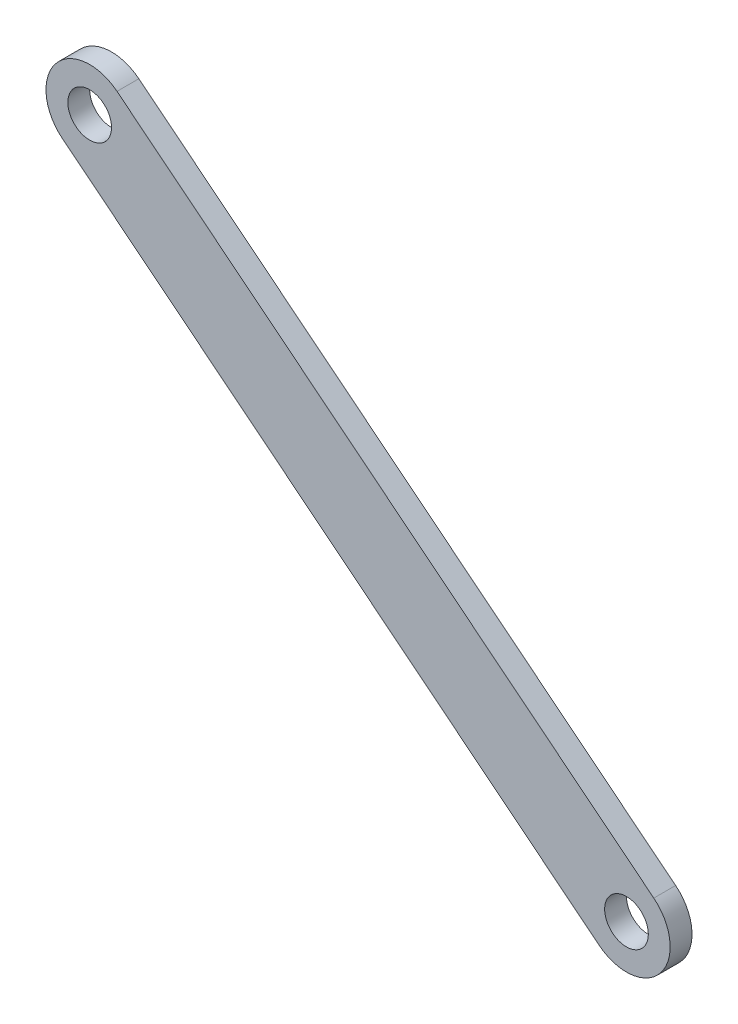
SolidWorks part; units mm, degrees
ref_plane "Front" through (0, 0, 0) normal (0, 0, 1) x (1, 0, 0)
ref_plane "Top" through (0, 0, 0) normal (0, 1, 0) x (1, 0, 0)
ref_plane "Right" through (0, 0, 0) normal (1, 0, 0) x (0, 0, -1)
sketch "Sketch1" plane through (0, 0, 0) normal (0, 0, 1) x (1, 0, 0)
  line L0 (-24.0135, 31.2721) -> (15, 0) construction
  line L1 (-22.0278, 33.7495) -> (16.9858, 2.4774)
  line L2 (-25.9993, 28.7947) -> (13.0142, -2.4774)
  arc A0 (-22.0278, 33.7495) -> (-25.9993, 28.7947) centre (-24.0135, 31.2721) ccw
  arc A1 (13.0142, -2.4774) -> (16.9858, 2.4774) centre (15, 0) ccw
  circle A2 centre (-24.0135, 31.2721) radius 1.5875
  circle A3 centre (15, 0) radius 1.5875
  point P4 (-4.5068, 15.636)
  dimension "D2" = 3.175
  dimension "D3" = 3.175
  dimension "D1" = 6.35
extrude "Boss-Extrude1" add sketch "Sketch1" along normal blind 1.5875
